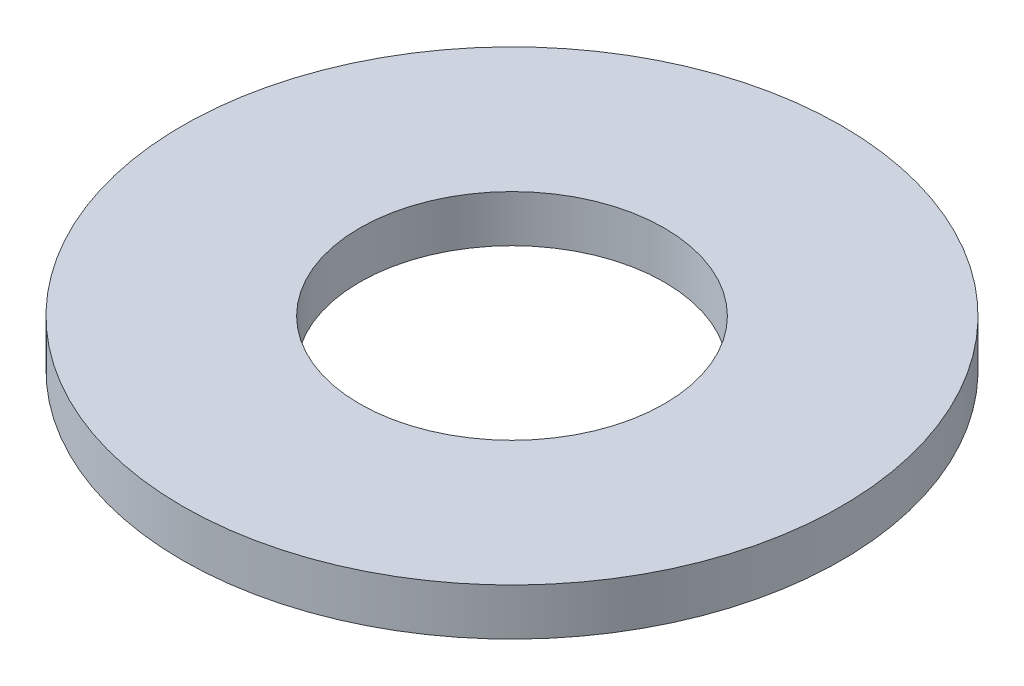
SolidWorks part; units mm, degrees
material "Brass"
ref_plane "Front Plane" through (0, 0, 0) normal (0, 0, 1) x (1, 0, 0)
ref_plane "Top Plane" through (0, 0, 0) normal (0, 1, 0) x (1, 0, 0)
ref_plane "Right Plane" through (0, 0, 0) normal (1, 0, 0) x (0, 0, -1)
sketch "Sketch1" plane through (0, 0, 0) normal (0, 1, 0) x (1, 0, 0)
  circle A0 centre (0, 0) radius 1.651
  circle A1 centre (0, 0) radius 3.5719
  dimension "D1" = 7.1437
  dimension "D2" = 3.302
extrude "Boss-Extrude1" add sketch "Sketch1" along normal mid plane 0.508
